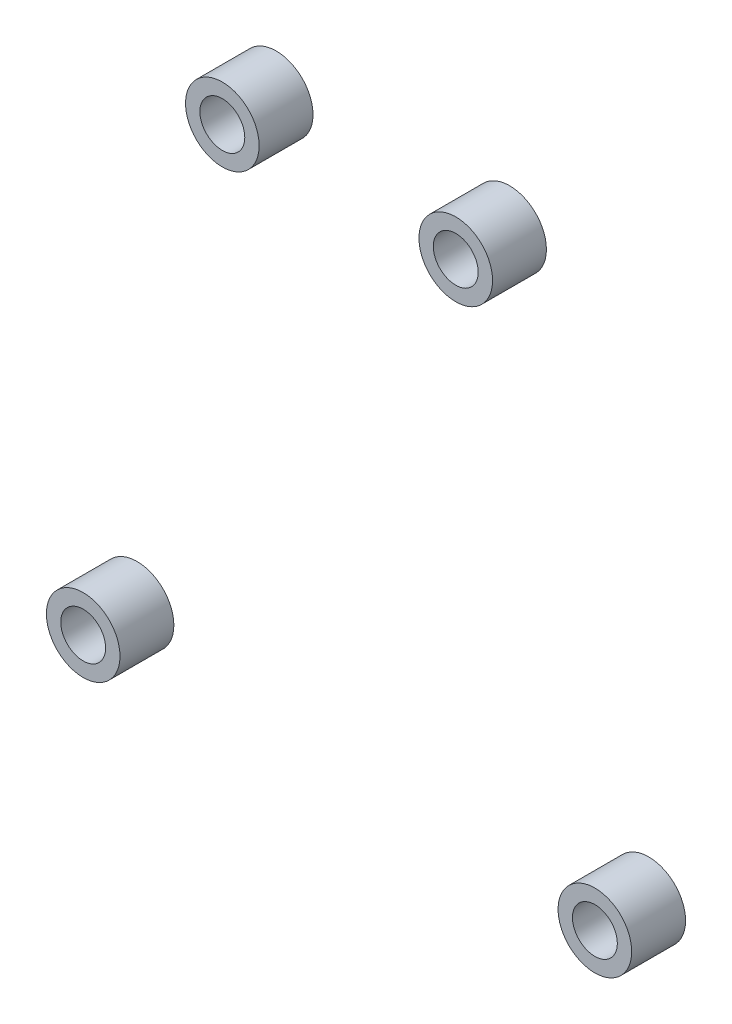
SolidWorks part; units mm, degrees
material "Винипласт"
ref_plane "Спереди" through (0, 0, 0) normal (0, 0, 1) x (1, 0, 0)
ref_plane "Сверху" through (0, 0, 0) normal (0, 1, 0) x (1, 0, 0)
ref_plane "Справа" through (0, 0, 0) normal (1, 0, 0) x (0, 0, -1)
sketch "Эскиз1" plane through (0, 0, 0) normal (0, 0, 1) x (1, 0, 0)
  point P0 (-6.5, 14.25)
  circle B0 centre (6.5, 14.25) radius 1.25
  circle B1 centre (6.5, 14.25) radius 2.05
  circle B2 centre (14.25, -14.25) radius 1.25
  circle B3 centre (14.25, -14.25) radius 2.05
  circle B4 centre (-14.25, -14.25) radius 1.25
  circle B5 centre (-14.25, -14.25) radius 2.05
  circle B6 centre (-6.5, 14.25) radius 1.25
  circle B7 centre (-6.5, 14.25) radius 2.05
sketch_block_instance "Блок1-1"
sketch_block "Блок1" parameters "D2"=2.5, "D1"=0.8
sketch_block_instance "Блок1-2"
sketch_block_instance "Блок1-3"
sketch_block_instance "Блок1-4"
extrude "Бобышка-Вытянуть1" add sketch "Эскиз1" along normal blind 3
